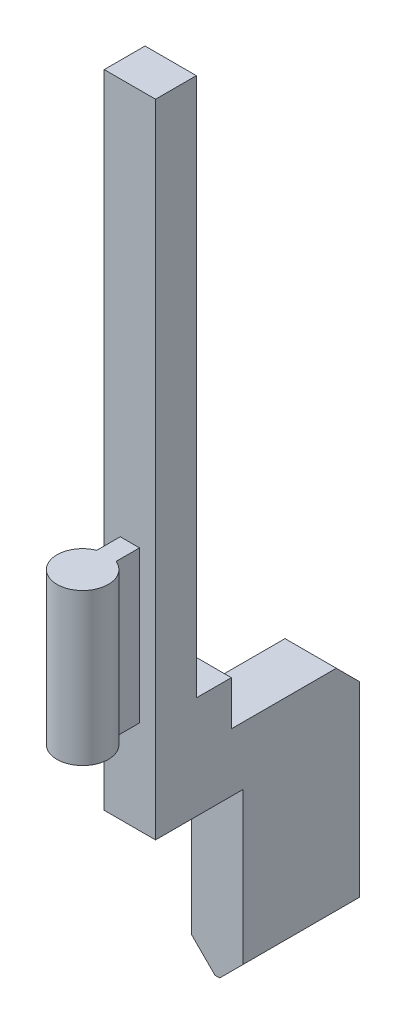
SolidWorks part; units mm, degrees
ref_plane "Płaszczyzna przednia" through (0, 0, 0) normal (0, 0, 1) x (1, 0, 0)
ref_plane "Płaszczyzna górna" through (0, 0, 0) normal (0, 1, 0) x (1, 0, 0)
ref_plane "Płaszczyzna prawa" through (0, 0, 0) normal (1, 0, 0) x (0, 0, -1)
sketch "Szkic1" plane through (0, 0, 0) normal (0, 0, 1) x (1, 0, 0)
  line L1 (-2.2, 10.5) -> (2.2, 10.5)
  line L2 (-2.2, 10.5) -> (-2.2, -10.5)
  line L3 (-2.2, -10.5) -> (2.2, -10.5)
  line L4 (2.2, 10.5) -> (2.2, -10.5)
  line L5 (-2.2, 10.5) -> (2.2, -10.5) construction
  line L6 (-2.2, -10.5) -> (2.2, 10.5) construction
  point P0 (0, 0)
  dimension "D1" = 4.4
  dimension "D2" = 21
extrude "Dodanie-wyciągnięcie1" add sketch "Szkic1" along normal blind 6.5
sketch "Szkic3" plane through (0, 10.5, 0) normal (0, 1, 0) x (1, 0, 0)
  line L0 (0, -6.5) -> (0, -10.55) construction
  line L1 (2.2, -6.5) -> (-2.2, -6.5) construction
  line L3 (0.825, -6.5) -> (0.825, -10.55)
  line L4 (0.825, -6.5) -> (-0.825, -6.5)
  line L5 (-0.825, -6.5) -> (-0.825, -10.55)
  line L6 (0.825, -10.55) -> (-0.825, -10.55)
  line L7 (0.825, -6.5) -> (-0.825, -10.55) construction
  line L8 (-0.825, -6.5) -> (0.825, -10.55) construction
  circle A0 centre (0, -10.55) radius 2.2
  point P5 (0, -8.525)
  line M10 (-2.2, 0) -> (-2.2, -6.5)
  dimension "D2" = 4.4
  dimension "D1" = 4.05
  dimension "D3" = 1.65
extrude "Dodanie-wyciągnięcie2" add sketch "Szkic3" against normal blind 13 contours L5 A0 L3 L6 | L3 A0 L5 L6 | A0 L3 L5 M10
sketch "Sketch1" plane through (0, 0, 0) normal (0, 0, -1) x (-1, 0, 0)
  line L0 (-2.2, -10.5) -> (-2.2, 10.5) construction
  line L1 (-2.2, -5.5) -> (2.2, -5.5)
  line L2 (-2.2, -5.5) -> (-2.2, -10.5)
  line L3 (-2.2, -10.5) -> (2.2, -10.5)
  line L4 (2.2, -5.5) -> (2.2, -10.5)
  line L5 (0, -10.5) -> (0, -5.5) construction
  line L6 (-2.2, -8) -> (2.2, -8) construction
  line L7 (2.2, 10.5) -> (2.2, -10.5) construction
  line L9 (2.2, -10.5) -> (-2.2, -10.5) construction
  point P460 (0, -8)
  dimension "D1" = 5
extrude "Boss-Extrude1" add sketch "Sketch1" along normal blind 11
sketch "Sketch3" plane through (0, -10.5, 0) normal (0, -1, 0) x (1, 0, 0)
  line L0 (2.2, -11) -> (-2.2, -11) construction
  line L1 (2.2, -11) -> (-2.2, -11)
  line L2 (2.2, -11) -> (2.2, -1)
  line L3 (2.2, -1) -> (-2.2, -1)
  line L4 (-2.2, -11) -> (-2.2, -1)
  line L5 (0, -1) -> (0, -11) construction
  line L6 (2.2, -6) -> (-2.2, -6) construction
  line L7 (2.2, 6.5) -> (2.2, -11) construction
  line L8 (-2.2, 6.5) -> (-2.2, -11) construction
  point P448 (0, -6)
  dimension "D2" = 10
extrude "Boss-Extrude3" add sketch "Sketch3" along normal blind 15
chamfer "Chamfer1" distance 2 angle 45 3 edges at (2.2, -25.5, -6) (-2.2, -25.5, -6) (0, -5.5, -11)
sketch "Sketch5" plane through (0, 10.5, 0) normal (0, 1, 0) x (1, 0, 0)
  line L0 (2.2, -6.5) -> (2.2, 0) construction
  line L1 (-2.2, 0) -> (2.2, 0)
  line L2 (-2.2, 0) -> (-2.2, -3)
  line L3 (-2.2, -3) -> (2.2, -3)
  line L4 (2.2, 0) -> (2.2, -3)
  line L5 (0, -3) -> (0, 0) construction
  line L6 (-2.2, -1.5) -> (2.2, -1.5) construction
  point P212 (0, -1.5)
  dimension "D1" = 3
extrude "Cut-Extrude1" cut sketch "Sketch5" against normal blind 12.2
sketch "Szkic4" plane through (0, 10.5, 0) normal (0, 1, 0) x (1, 0, 0)
  line L0 (-2.2, -6.5) -> (-2.2, -3) construction
  line L1 (-2.2, -3) -> (2.2, -3)
  line L2 (-2.2, -3) -> (-2.2, -6.5)
  line L3 (-2.2, -6.5) -> (2.2, -6.5)
  line L4 (2.2, -3) -> (2.2, -6.5)
  line L5 (-2.2, -3) -> (2.2, -3) construction
  line L6 (2.2, -6.5) -> (2.2, -3) construction
extrude "Dodanie-wyciągnięcie3" add sketch "Szkic4" along normal blind 34
